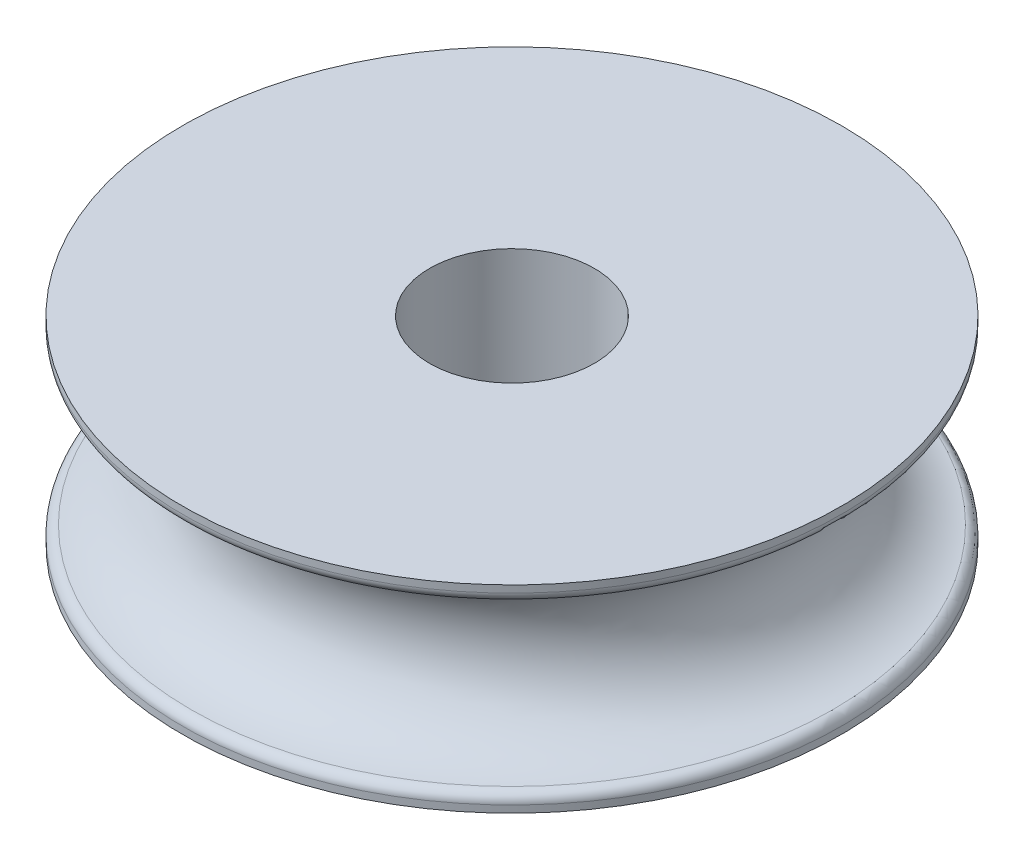
SolidWorks part; units mm, degrees
ref_plane "Front Plane" through (0, 0, 0) normal (0, 0, 1) x (1, 0, 0)
ref_plane "Top Plane" through (0, 0, 0) normal (0, 1, 0) x (1, 0, 0)
ref_plane "Right Plane" through (0, 0, 0) normal (1, 0, 0) x (0, 0, -1)
sketch "Sketch2" plane through (0, 0, 0) normal (0, 0, 1) x (1, 0, 0)
  line L0 (0, 0) -> (0, 45.196) construction
  line L1 (0, 0) -> (10, 0)
  line L2 (10, 0) -> (10, 0.2161)
  line L3 (10, 6) -> (0, 6)
  line L4 (10, 5.7839) -> (10, 6)
  line L5 (0, 0) -> (0, 6)
  arc A0 (9.7321, 5.4856) -> (9.7321, 0.5144) centre (10, 3) ccw
  arc A1 (9.7321, 0.5144) -> (10, 0.2161) centre (9.7, 0.2161) cw
  arc A2 (9.7321, 5.4856) -> (10, 5.7839) centre (9.7, 5.7839) ccw
  point P13 (10, 5.5)
  dimension "D3" = 5
  dimension "D4" = 0.3
  dimension "D1" = 10
  dimension "D2" = 6
revolve "Revolve1" add sketch "Sketch2" angle 360 about L0
sketch "Sketch3" plane through (0, 6, 0) normal (0, 1, 0) x (1, 0, 0)
  circle A0 centre (0, 0) radius 2.5
extrude "Cut-Extrude1" cut sketch "Sketch3" against normal blind 10
